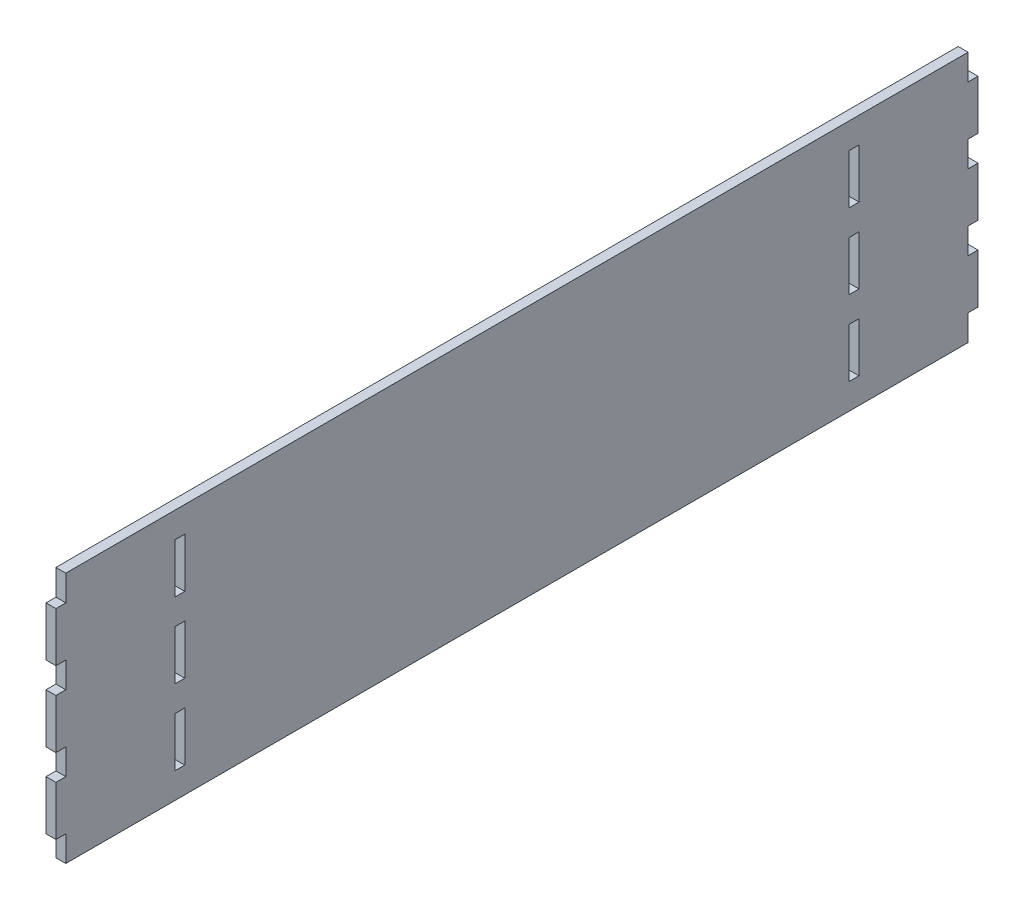
SolidWorks part; units mm, degrees
material "ENPH 253 Hardboard"
ref_plane "Front Plane" through (0, 0, 0) normal (0, 0, 1) x (1, 0, 0)
ref_plane "Top Plane" through (0, 0, 0) normal (0, 1, 0) x (1, 0, 0)
ref_plane "Right Plane" through (0, 0, 0) normal (1, 0, 0) x (0, 0, -1)
sketch "Sketch1" plane through (0, 0, 0) normal (1, 0, 0) x (0, 0, -1)
  line L1 (-139.7, 38.1) -> (139.7, 38.1)
  line L2 (-139.7, 38.1) -> (-139.7, -38.1)
  line L3 (-139.7, -38.1) -> (139.7, -38.1)
  line L4 (139.7, 38.1) -> (139.7, -38.1)
  line L5 (-139.7, 38.1) -> (139.7, -38.1) construction
  line L6 (-139.7, -38.1) -> (139.7, 38.1) construction
  point P0 (0, 0)
  dimension "D1" = 279.4
  dimension "D2" = 76.2
extrude "Boss-Extrude1" add sketch "Sketch1" against normal blind 3 contours L2 L3 L4 L1
sketch "Sketch3" plane through (-3, 0, 0) normal (-1, 0, 0) x (0, 0, 1)
  line L2 (-139.7, 38.1) -> (-139.7, -38.1) construction
  line L7 (-100.65, 30.3) -> (-103.65, 30.3)
  line L8 (-100.65, 30.3) -> (-100.65, 15.3)
  line L9 (-139.7, 38.1) -> (-136.7, 38.1)
  line L10 (-139.7, 38.1) -> (-139.7, 30.3)
  line L11 (-139.7, 30.3) -> (-136.7, 30.3)
  line L12 (-136.7, 38.1) -> (-136.7, 30.3)
  line L13 (-100.65, 15.3) -> (-103.65, 15.3)
  line L14 (-103.65, 30.3) -> (-103.65, 15.3)
  line L15 (139.7, 38.1) -> (-139.7, 38.1) construction
  dimension "D5" = 15
  dimension "D6" = 3
  dimension "D7" = 36.05
  dimension "D8" = 7.8
  dimension "D9" = 7.8
  dimension "D10" = 3
extrude "Cut-Extrude1" cut sketch "Sketch3" against normal through all
pattern_linear "LPattern1" count 4 spacing 22.8 along (0, -1, 0) of "Cut-Extrude1"
mirror "Mirror1" about plane through (0, 0, 0) normal (0, 0, 1) of "LPattern1", "Cut-Extrude1"
